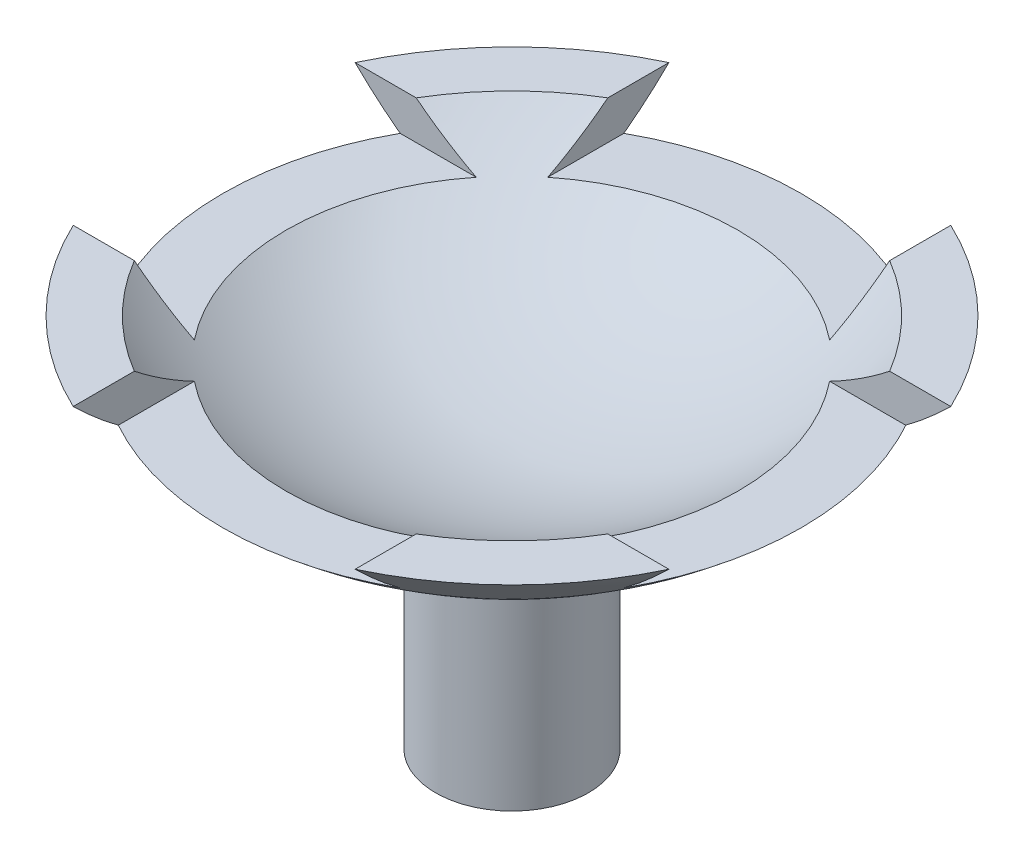
SolidWorks part; units mm, degrees
ref_plane "Front Plane" through (0, 0, 0) normal (0, 0, 1) x (1, 0, 0)
ref_plane "Top Plane" through (0, 0, 0) normal (0, 1, 0) x (1, 0, 0)
ref_plane "Right Plane" through (0, 0, 0) normal (1, 0, 0) x (0, 0, -1)
sketch "Sketch1" plane through (0, 0, 0) normal (0, 0, 1) x (1, 0, 0)
  line L0 (0, 0) -> (0, 21)
  line L1 (21.6111, 29.4) -> (25.8465, 29.4)
  line L2 (6, 18.5181) -> (6, 0)
  line L3 (6, 0) -> (0, 0)
  arc A0 (6, 18.5181) -> (25.8465, 29.4) centre (0, 53) ccw
  arc A1 (0, 21) -> (21.6111, 29.4) centre (0, 53) ccw
  arc A2 (0.7795, 21.0095) -> (24.1613, 73.9817) centre (0, 53) ccw construction
  arc A3 (0.8525, 18.0104) -> (26.4264, 75.9487) centre (0, 53) ccw construction
  point P6 (0, 0)
  dimension "D5" = 35
  dimension "D2" = 29.4
  dimension "D3" = 21
  dimension "D4" = 6
  dimension "D1" = 3
revolve "Revolve1" add sketch "Sketch1" angle 360 about L0
sketch "Sketch2" plane through (0, 0, 0) normal (0, 0, 1) x (1, 0, 0)
  line L0 (25.8465, 29.4) -> (-25.8465, 29.4) construction
  line L1 (-11.055, 29.4) -> (11.055, 29.4)
  line L2 (-11.055, 29.4) -> (-11.055, 26.36)
  line L3 (-11.055, 26.36) -> (11.055, 26.36)
  line L4 (11.055, 29.4) -> (11.055, 26.36)
  line L5 (0, 0) -> (0, 34.1873) construction
  line L6 (-6, 0) -> (6, 0) construction
  dimension "D1" = 3.04
  dimension "D2" = 22.11
extrude "Cut-Extrude1" cut sketch "Sketch2" against normal blind 10 and the other way through all
pattern_circular "CirPattern1" count 4 over 360 about axis through (0, 0, 0) along (0, 1, 0) of "Cut-Extrude1"
fillet "Fillet1" radius 1.5 1 edges at (0, 18.5181, -6)
